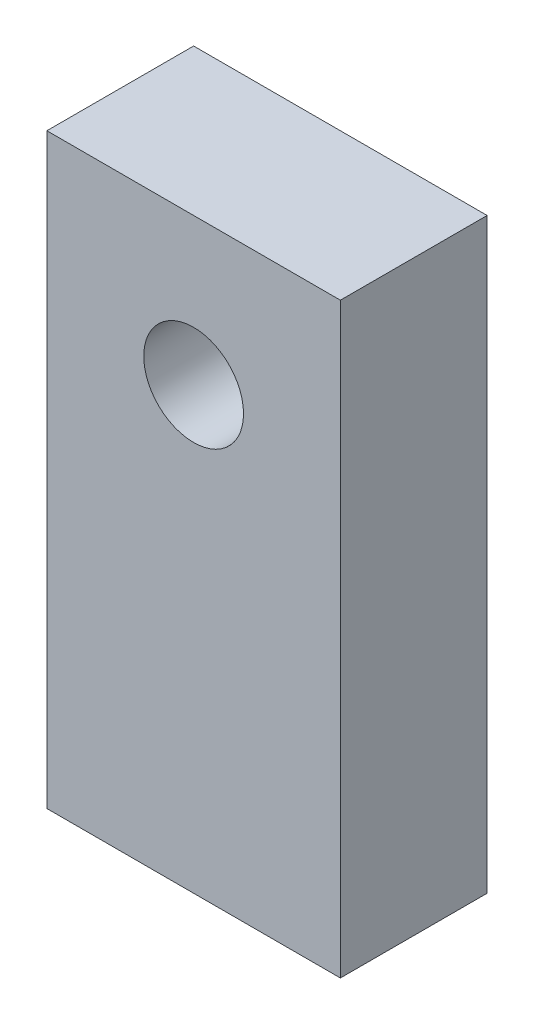
SolidWorks part; units mm, degrees
ref_plane "Front Plane" through (0, 0, 0) normal (0, 0, 1) x (1, 0, 0)
ref_plane "Top Plane" through (0, 0, 0) normal (0, 1, 0) x (1, 0, 0)
ref_plane "Right Plane" through (0, 0, 0) normal (1, 0, 0) x (0, 0, -1)
sketch "Sketch1" plane through (0, 0, 0) normal (0, 0, 1) x (1, 0, 0)
  line L1 (-15, 15) -> (15, 15)
  line L2 (-15, 15) -> (-15, -45)
  line L3 (-15, -45) -> (15, -45)
  line L4 (15, 15) -> (15, -45)
  dimension "D1" = 15
  dimension "D2" = 15
  dimension "D3" = 15
  dimension "D4" = 45
extrude "Boss-Extrude1" add sketch "Sketch1" along normal mid plane 15
sketch "Sketch2" plane through (0, 0, 0) normal (0, 0, 1) x (1, 0, 0)
  circle A0 centre (0, 0) radius 5.1
  dimension "D1" = 10.2
extrude "Cut-Extrude1" cut sketch "Sketch2" against normal through all both and the other way through all
